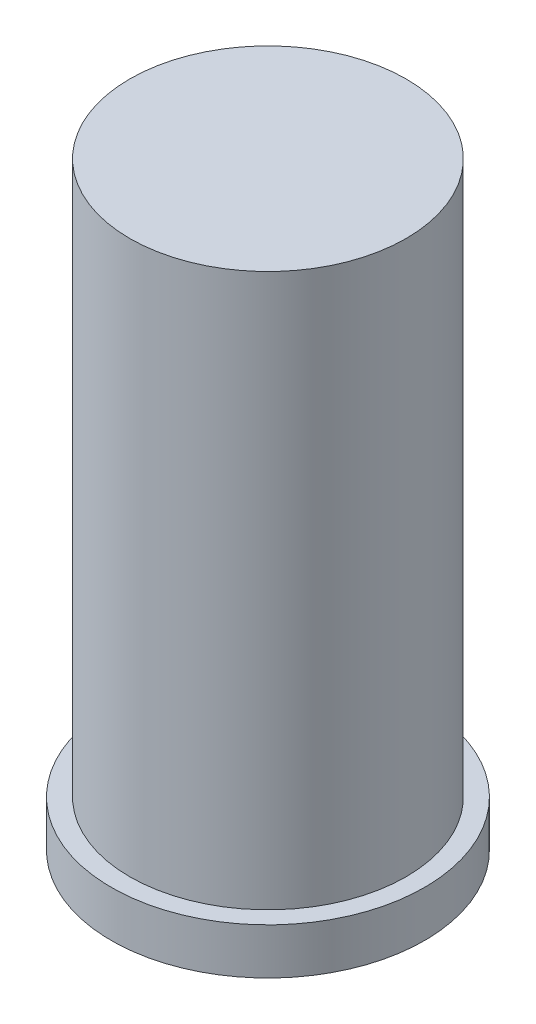
SolidWorks part; units mm, degrees
ref_plane "Front Plane" through (0, 0, 0) normal (0, 0, 1) x (1, 0, 0)
ref_plane "Top Plane" through (0, 0, 0) normal (0, 1, 0) x (1, 0, 0)
ref_plane "Right Plane" through (0, 0, 0) normal (1, 0, 0) x (0, 0, -1)
sketch "Sketch1" plane through (0, 0, 0) normal (0, 1, 0) x (1, 0, 0)
  circle A0 centre (0, 0) radius 1.5
  dimension "D1" = 3
extrude "Boss-Extrude1" add sketch "Sketch1" along normal blind 6 contours A0
sketch "Sketch2" plane through (0, 0, 0) normal (0, -1, 0) x (1, 0, 0)
  circle A0 centre (0, 0) radius 1.7
  dimension "D1" = 3.4
extrude "Boss-Extrude2" add sketch "Sketch2" along normal blind 0.5 contours A0
